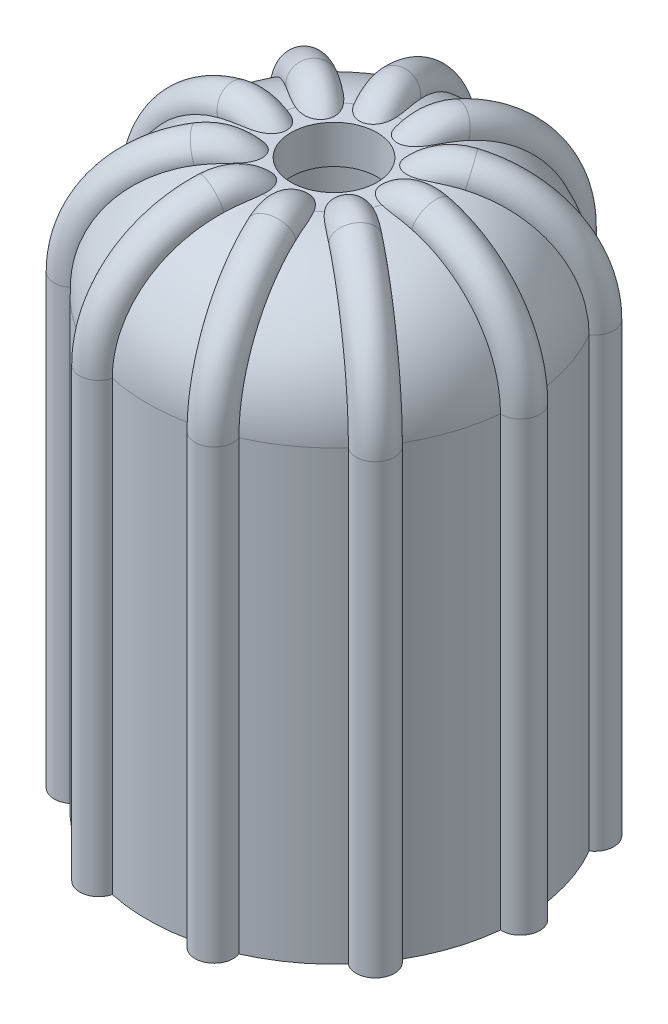
SolidWorks part; units mm, degrees
ref_plane "Спереди" through (0, 0, 0) normal (0, 0, 1) x (1, 0, 0)
ref_plane "Сверху" through (0, 0, 0) normal (0, 1, 0) x (1, 0, 0)
ref_plane "Справа" through (0, 0, 0) normal (1, 0, 0) x (0, 0, -1)
sketch "Эскиз1" plane through (0, 0, 0) normal (0, 0, 1) x (1, 0, 0)
  line L0 (0, 0) -> (0, 5929.2763) construction
  line L1 (-3.5, 21.6) -> (-3.5, 27.6)
  line L3 (-9.75, 23.35) -> (-9.75, 0)
  line L4 (-9.75, 0) -> (-8.75, 0)
  line L5 (-8.75, 0) -> (-8.75, 20)
  line L6 (-6.25, 21.6) -> (-3.5, 21.6)
  line L10 (-6.25, 21.6) -> (-6.25, 20)
  line L11 (-6.25, 20) -> (-8.75, 20)
  line L12 (-3.5, 27.6) -> (-2.25, 27.6)
  line L13 (-2.25, 27.6) -> (-2.25, 29.6)
  line L14 (-2.25, 29.6) -> (-3.5, 29.6)
  arc A2 (-3.5, 29.6) -> (-9.75, 23.35) centre (-3.5, 23.35) ccw
  dimension "D1" = 1
  dimension "D2" = 6
  dimension "D3" = 7
  dimension "D4" = 20
  dimension "D5" = 12.5
  dimension "D6" = 2.5
  dimension "D7" = 1.6
  dimension "D8" = 2
  dimension "D9" = 4.5
revolve "Повернуть1" add sketch "Эскиз1" angle 360 about L0
sketch "Эскиз2" plane through (0, 0, 0) normal (0, 0, 1) x (1, 0, 0)
  line L0 (-9.75, 23.35) -> (-9.75, 0) construction
  line L1 (-9.75, 23.35) -> (-9.75, 0)
  line L3 (0, 29.6) -> (0, 23.35) construction
  line L4 (0, 23.35) -> (-9.75, 23.35) construction
  line L5 (0, 23.35) -> (-5.0751, 29.3983) construction
  arc A0 (-3.5, 29.6) -> (-9.75, 23.35) centre (-3.5, 23.35) ccw construction
  arc A1 (-5.0751, 29.3983) -> (-9.75, 23.35) centre (-3.5, 23.35) ccw
  arc A2 (-5.0751, 29.3983) -> (-3.1286, 28.8482) centre (-4.5711, 27.4628) cw
  point P10 (-3.1286, 28.8482)
  dimension "D1" = 50
  dimension "D2" = 2
sketch "Эскиз3" plane through (0, 0, 0) normal (0, -1, 0) x (-1, 0, 0)
  circle A0 centre (9.75, 0) radius 1
  dimension "D1" = 2
sweep "По траектории1" add profiles "Эскиз3" path "Эскиз2"
pattern_circular "Круговой массив1" count 10 over 360 about axis through (0, 0, 0) along (0, 1, 0) of "По траектории1"
